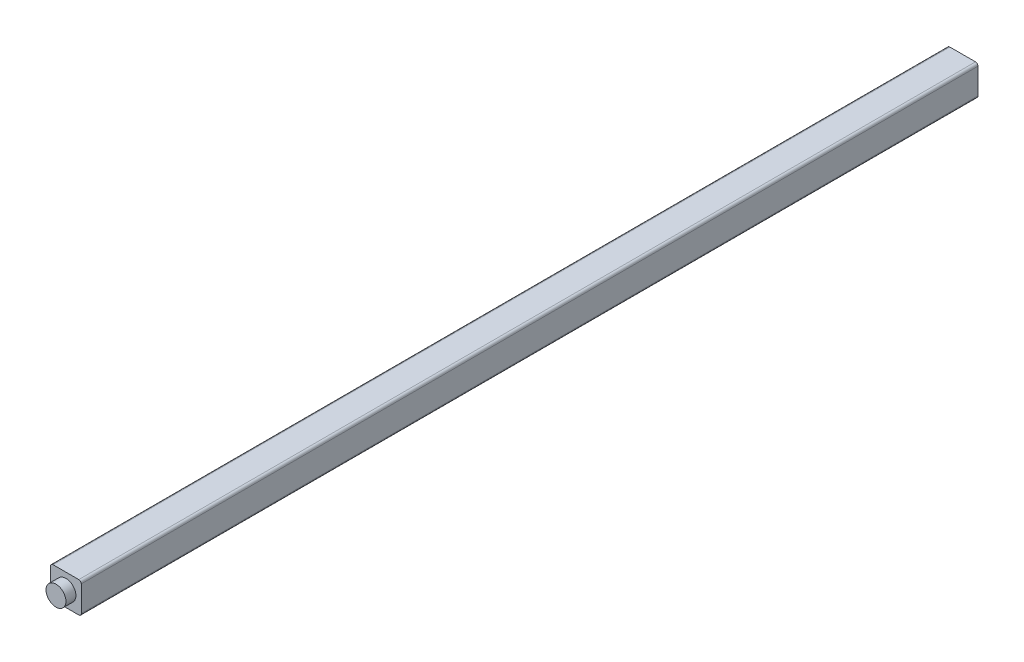
SolidWorks part; units mm, degrees
ref_plane "Front" through (0, 0, 0) normal (0, 0, 1) x (1, 0, 0)
ref_plane "Top" through (0, 0, 0) normal (0, 1, 0) x (1, 0, 0)
ref_plane "Right" through (0, 0, 0) normal (1, 0, 0) x (0, 0, -1)
sketch "Sketch2" plane through (0, 0, 0) normal (0, 0, 1) x (1, 0, 0)
  line L1 (0.25, 0) -> (2.83, 0)
  line L2 (0, 0.25) -> (0, 2.83)
  line L3 (0.25, 3.08) -> (2.83, 3.08)
  line L4 (3.08, 0.25) -> (3.08, 2.83)
  arc A0 (2.83, 0) -> (3.08, 0.25) centre (2.83, 0.25) ccw
  arc A1 (0, 0.25) -> (0.25, 0) centre (0.25, 0.25) ccw
  arc A2 (2.83, 3.08) -> (3.08, 2.83) centre (2.83, 2.83) cw
  arc A3 (0.25, 3.08) -> (0, 2.83) centre (0.25, 2.83) ccw
  point P9 (0, 0)
  dimension "D1" = 0.25
extrude "Boss-Extrude1" add sketch "Sketch2" along normal blind 90
sketch "Sketch3" plane through (0, 0, 90) normal (0, 0, 1) x (1, 0, 0)
  line L0 (1.54, 3.08) -> (1.54, 0) construction
  line L1 (2.83, 3.08) -> (0.25, 3.08) construction
  line L2 (0.25, 0) -> (2.83, 0) construction
  line L3 (0, 1.54) -> (3.08, 1.54) construction
  line L4 (0, 2.83) -> (0, 0.25) construction
  line L5 (3.08, 0.25) -> (3.08, 2.83) construction
  circle A0 centre (1.54, 1.54) radius 1
extrude "Boss-Extrude2" add sketch "Sketch3" along normal blind 1
